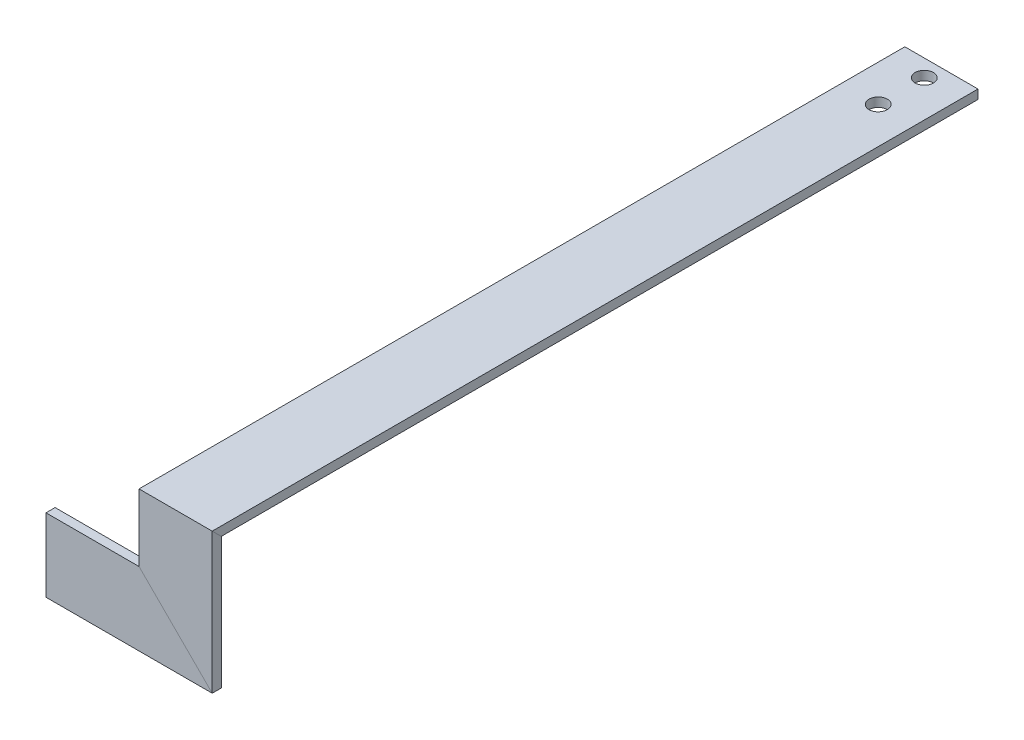
SolidWorks part; units mm, degrees
ref_plane "Alzado" through (0, 0, 0) normal (0, 0, 1) x (1, 0, 0)
ref_plane "Planta" through (0, 0, 0) normal (0, 1, 0) x (1, 0, 0)
ref_plane "Vista lateral" through (0, 0, 0) normal (1, 0, 0) x (0, 0, -1)
sketch "Croquis1" plane through (0, 0, 0) normal (0, 0, 1) x (1, 0, 0)
  line L1 (-25.4, 3.155) -> (25.4, 3.155)
  line L2 (-25.4, 3.155) -> (-25.4, -3.155)
  line L3 (-25.4, -3.155) -> (25.4, -3.155)
  line L4 (25.4, 3.155) -> (25.4, -3.155)
  line L5 (-25.4, 3.155) -> (25.4, -3.155) construction
  line L6 (-25.4, -3.155) -> (25.4, 3.155) construction
  point P0 (0, 0)
  dimension "D1" = 50.8
  dimension "D2" = 6.31
sketch3d "Croquis3D1"
  line L0 (0, 0, 0) -> (0, 0, 528.55)
  line L1 (0, 0, 528.55) -> (0, -68.92, 528.55)
  line L2 (0, -68.92, 528.55) -> (-90, -68.92, 528.55)
  dimension "D1" = 528.55
  dimension "D2" = 68.92
  dimension "D3" = 90
sweep "Barrer1" add profiles "Croquis1" path "Croquis3D1"
sketch "Croquis2" plane through (0, 3.155, 0) normal (0, 1, 0) x (1, 0, 0)
  circle A0 centre (0, -43.8922) radius 6.35
  circle A1 centre (0, -11.8922) radius 6.35
extrude "Cortar-Extruir1" cut sketch "Croquis2" against normal blind 6.31
